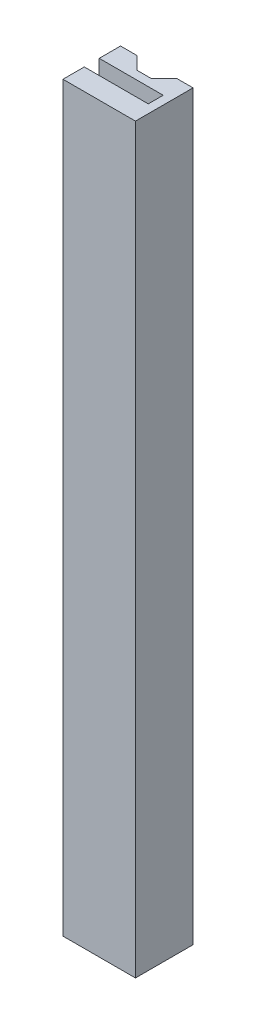
SolidWorks part; units mm, degrees
ref_plane "Front Plane" through (0, 0, 0) normal (0, 0, 1) x (1, 0, 0)
ref_plane "Top Plane" through (0, 0, 0) normal (0, 1, 0) x (1, 0, 0)
ref_plane "Right Plane" through (0, 0, 0) normal (1, 0, 0) x (0, 0, -1)
sketch "Sketch1" plane through (0, 0, 0) normal (0, 1, 0) x (1, 0, 0)
  line L0 (-8.4981, 13.5) -> (-4.6481, 13.5)
  line L1 (-4.6481, 13.5) -> (-1.65, 10.5019)
  line L2 (-1.65, 10.5019) -> (1.65, 10.5019)
  line L3 (1.65, 10.5019) -> (4.6481, 13.5)
  line L4 (4.6481, 13.5) -> (8.4981, 13.5)
  line L5 (8.4981, 13.5) -> (8.4981, 0)
  line L6 (8.4981, 0) -> (-8.4981, 0)
  line L7 (-8.4981, 0) -> (-8.4981, 5)
  line L8 (-8.4981, 5) -> (6.5019, 5)
  line L9 (6.5019, 5) -> (6.5019, 8.5)
  line L10 (6.5019, 8.5) -> (-8.4981, 8.5)
  line L11 (-8.4981, 8.5) -> (-8.4981, 13.5)
  dimension "D1" = 15
  dimension "D2" = 5
  dimension "D3" = 3.5
  dimension "D4" = 5
  dimension "D5" = 3.85
  dimension "D6" = 3.3
  dimension "D7" = 4.24
  dimension "D8" = 4.24
extrude "Boss-Extrude1" add sketch "Sketch1" along normal blind 174
